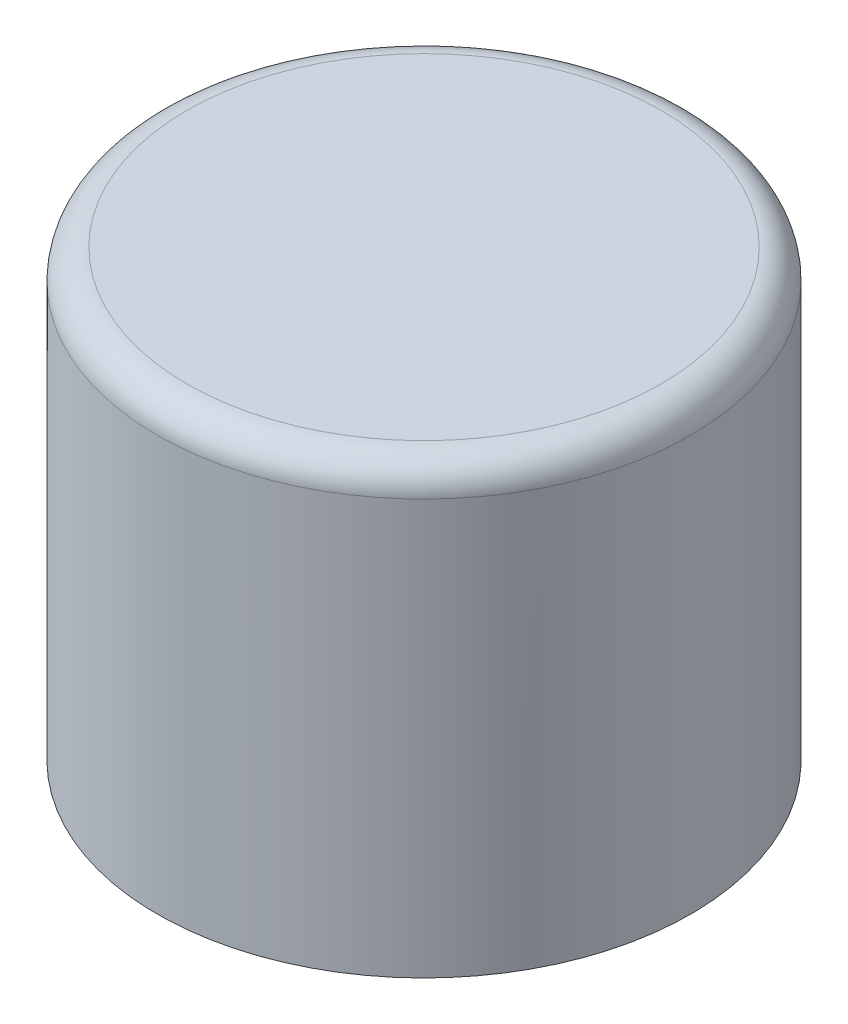
SolidWorks part; units mm, degrees
ref_plane "Front Plane" through (0, 0, 0) normal (0, 0, 1) x (1, 0, 0)
ref_plane "Top Plane" through (0, 0, 0) normal (0, 1, 0) x (1, 0, 0)
ref_plane "Right Plane" through (0, 0, 0) normal (1, 0, 0) x (0, 0, -1)
sketch "Sketch1" plane through (0, 0, 0) normal (0, 0, 1) x (1, 0, 0)
  line L0 (4, 0) -> (8, 0)
  line L1 (0, 0) -> (2.5, 0)
  line L2 (0, 0) -> (0, 2.5)
  line L3 (0, 2.5) -> (9, 2.5)
  line L4 (9, 0) -> (9, 2.5)
  line L6 (9, 0) -> (9, -12.5)
  line L7 (9, -12.5) -> (8, -12.5)
  line L8 (8, 0) -> (8, -12.5)
  line L10 (2.5, 0) -> (2.5, -4)
  line L11 (2.5, -4) -> (4, -4)
  line L12 (4, 0) -> (4, -4)
  dimension "D1" = 9
  dimension "D2" = 1
  dimension "D3" = 1.5
  dimension "D4" = 2.5
  dimension "D5" = 2.5
  dimension "D6" = 15
  dimension "D7" = 4
revolve "Revolve1" add sketch "Sketch1" angle 360 about L2
fillet "Fillet1" radius 1 2 edges at (0, 0, -8) (0, 2.5, -9)
